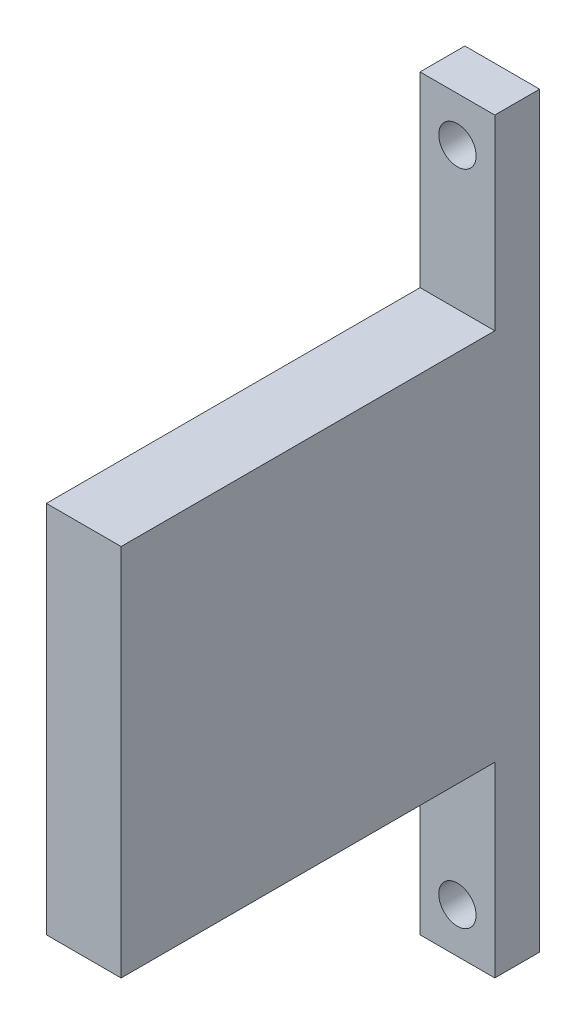
SolidWorks part; units mm, degrees
material "6063-T5"
ref_plane "前视基准面" through (0, 0, 0) normal (0, 0, 1) x (1, 0, 0)
ref_plane "上视基准面" through (0, 0, 0) normal (0, 1, 0) x (1, 0, 0)
ref_plane "右视基准面" through (0, 0, 0) normal (1, 0, 0) x (0, 0, -1)
sketch "草图1" plane through (0, 0, 0) normal (1, 0, 0) x (0, 0, -1)
  line L0 (25, 25) -> (25, 37.5)
  line L1 (0, 0) -> (25, 0)
  line L2 (0, 0) -> (0, 25)
  line L3 (0, 25) -> (25, 25)
  line L5 (25, -12.5) -> (28, -12.5)
  line L6 (25, -12.5) -> (25, 0)
  line L7 (25, 37.5) -> (28, 37.5)
  line L8 (28, -12.5) -> (28, 37.5)
  point P9 (28, 12.5)
  point P10 (0, 12.5)
  dimension "D1" = 3
  dimension "D2" = 25
  dimension "D3" = 50
  dimension "D4" = 25
extrude "凸台-拉伸2" add sketch "草图1" along normal blind 5
sketch "草图2" plane through (0, 0, -25) normal (0, 0, 1) x (1, 0, 0)
  line L0 (0, 12.5) -> (5, 12.5) construction
  line L1 (0, 25) -> (0, 0) construction
  line L2 (5, 25) -> (5, 0) construction
  line L3 (5, 37.5) -> (0, 37.5) construction
  circle A0 centre (2.5, 34.5) radius 1.25
  circle A1 centre (2.5, -9.5) radius 1.25
  point P10 (2.5, 37.5)
  dimension "D1" = 3
  dimension "D2" = 2.5
extrude "切除-拉伸1" cut sketch "草图2" against normal blind 4
sketch "草图3" plane through (0, 0, 0) normal (-1, 0, 0) x (0, 0, 1)
  line L0 (-28, -12.5) -> (-28, 37.5) construction
  line L1 (-28, 37.5) -> (-25, 37.5) construction
  circle A0 centre (-8, 12.5) radius 5.05
  dimension "D1" = 20
  dimension "D3" = 10.1
  dimension "D2" = 25
extrude "切除-拉伸2" cut sketch "草图3" against normal blind 3
chamfer "倒角1" distance 0.5 angle 45 1 edges at (0, 12.5, -2.95)
